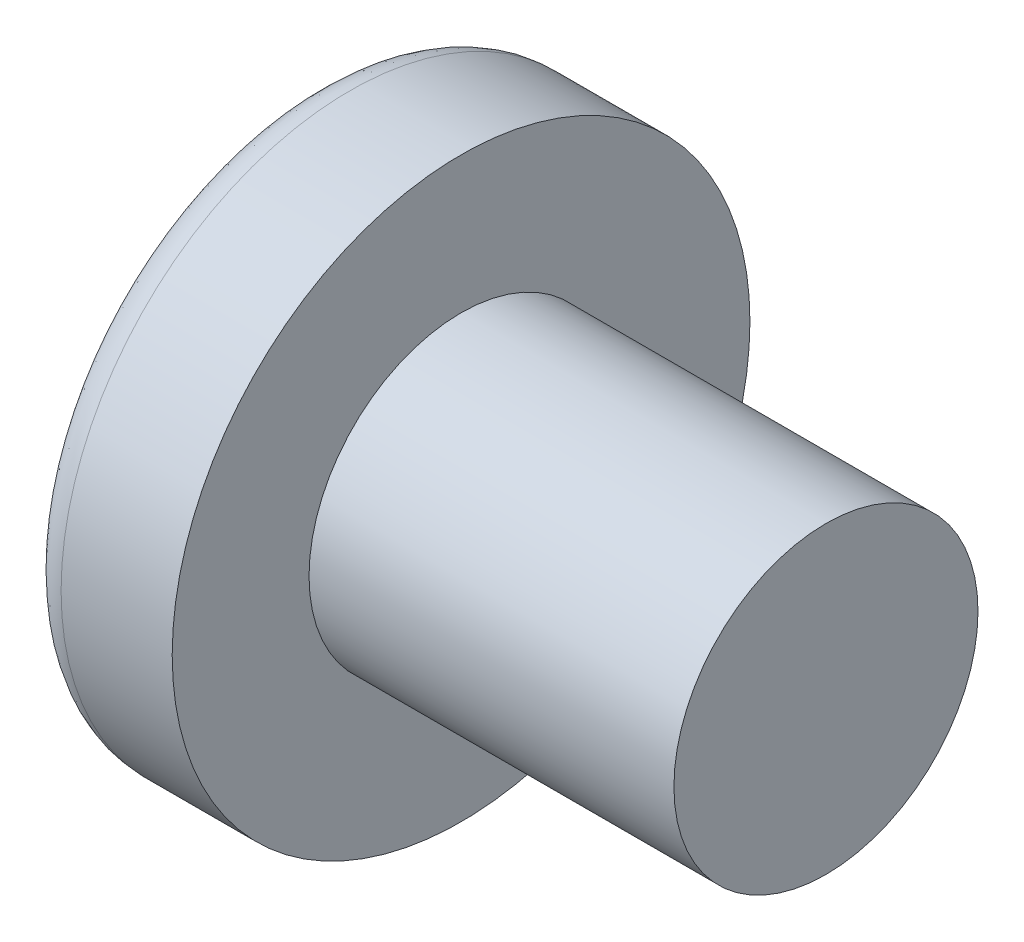
SolidWorks part; units mm, degrees
ref_plane "Plane1" through (0, 0, 0) normal (0, 0, 1) x (1, 0, 0)
ref_plane "Plane2" through (0, 0, 0) normal (0, 1, 0) x (1, 0, 0)
ref_plane "Plane3" through (0, 0, 0) normal (1, 0, 0) x (0, 0, -1)
sketch "BodySke" plane through (0, 0, 0) normal (0, 0, 1) x (1, 0, 0)
  line L0 (3.7, 2.5) -> (3.7, 4.75)
  line L1 (4.5, 6.35) -> (4.5, -3.175) construction
  line L2 (-25.4, 0) -> (127, 0) construction
  line L3 (9.7, 0) -> (0, 0)
  line L4 (3.7, 2.5) -> (9.7, 2.5)
  line L5 (9.7, 2.5) -> (9.7, 0)
  line L6 (1.8732, 4.75) -> (3.7, 4.75)
  line L7 (3.7, -2.5) -> (9.7, -2.5) construction
  line L8 (3.7, 6.35) -> (3.7, -3.175) construction
  arc A0 (1.3764, 4.4865) -> (0, 0) centre (8, 0) ccw
  arc A2 (1.3764, 4.4865) -> (1.8732, 4.75) centre (1.8732, 4.15) cw
  dimension "Head_crown_rad" = 8
  dimension "Head_fillet_rad" = 0.6
  dimension "Diameter" = 5
  dimension "Length" = 6
  dimension "Head_ht" = 3.7
  dimension "Head_dia" = 9.5
  dimension "Advance" = 0.8
  dimension "Thread_nom" = 6
revolve "Base-Revolve" add sketch "BodySke" angle 360 about L2
cosmetic thread "ThreadCosmetic" [suppressed] parameters "Thread_length"=5.2, "Thread_minor"=4.11
sketch "Sketch3" plane through (0, 0, 0) normal (1, 0, 0) x (0, 0, -1)
  line L0 (0.5, -2.45) -> (-0.5, -2.45)
  line L1 (0.5, -2.45) -> (0.5, 2.45)
  line L2 (-0.5, 2.45) -> (0.5, 2.45)
  line L3 (-0.5, 2.45) -> (-0.5, -2.45)
  dimension "Cross_dia" = 4.9
  dimension "D1" = 2.45
  dimension "Cross_width" = 1
  dimension "D2" = 0.5
ref_plane "Plane4" through (2.95, 0, 0) normal (1, 0, 0) x (0, 0, -1)
sketch "Sketch4" plane through (2.95, 0, 0) normal (1, 0, 0) x (0, 0, -1)
  line L0 (0.25, -0.25) -> (-0.25, -0.25)
  line L1 (0.25, -0.25) -> (0.25, 0.25)
  line L2 (-0.25, 0.25) -> (0.25, 0.25)
  line L3 (-0.25, 0.25) -> (-0.25, -0.25)
  dimension "D2" = 0.5
  dimension "D1" = 0.5
  dimension "D3" = 0.25
  dimension "D4" = 0.25
loft "Cut-Loft1" cut profiles "Sketch3", "Sketch4"
pattern_circular "CirPattern1" count 2 every 90 about axis through (0, 0, 0) along (1, 0, 0) of "Cut-Loft1"
sketch "ThdSchSke" plane through (0, 0, 0) normal (0, 0, 1) x (1, 0, 0)
  line L0 (4.5, -2.055) -> (4.1884, -2.5)
  line L1 (4.5, -2.055) -> (4.8116, -2.5)
  line L2 (4.8116, -2.5) -> (4.8116, -3.125)
  line L3 (-3.175, 0) -> (5.1513, 0) construction
  line L5 (4.8116, -3.125) -> (4.1884, -3.125)
  line L6 (4.1884, -3.125) -> (4.1884, -2.5)
  dimension "Diameter" = 5
  dimension "SideAngle" = 55
  dimension "VeeAngle" = 70
  dimension "Thread_minor" = 4.11
  dimension "Overcut" = 6.25
  dimension "Start" = 4.5
revolve "ThreadSchematic" [suppressed] cut sketch "ThdSchSke" angle 360 about L3
pattern_linear "ThdSchPat" [suppressed]
equation "\"D1@Sketch3\" = \"Cross_dia@Sketch3\" / 2"
equation "\"D2@Sketch3\" = \"Cross_width@Sketch3\" / 2"
equation "\"D1@Sketch4\" = \"Cross_width@Sketch3\" *.5"
equation "\"D2@Sketch4\" = \"D1@Sketch4\""
equation "\"D3@Sketch4\" = \"D1@Sketch4\" / 2"
equation "\"D4@Sketch4\" = \"D2@Sketch4\" / 2"
equation "\"Thread_length@ThreadCosmetic\" = ((sgn( (\"Length@BodySke\" - \"Advance@BodySke\" ) - \"Thread_nom@BodySke\" )-1)*( (\"Length@BodySke\" - \"Advance@BodySke\" ) - \"Thread_nom@BodySke\" ))/-2+ \"Thread_nom@BodySke\""
equation "\"Thread_minor@ThdSchSke\" = \"Thread_minor@ThreadCosmetic\""
equation "\"Diameter@ThdSchSke\" = \"Diameter@BodySke\""
equation "\"Overcut@ThdSchSke\" = \"Diameter@BodySke\" * 1.25"
equation "\"Start@ThdSchSke\" = \"Head_ht@BodySke\" + \"Length@BodySke\" - \"Thread_length@ThreadCosmetic\"  '---Non-countersunk---"
equation "\"Num_threads@ThdSchPat\" = int( \"Thread_length@ThreadCosmetic\" / \"Advance@BodySke\" + 0.999 )  + 1"
equation "\"Advance@ThdSchPat\" = \"Thread_length@ThreadCosmetic\" /  (\"Num_threads@ThdSchPat\" - 1) 'relax it"
